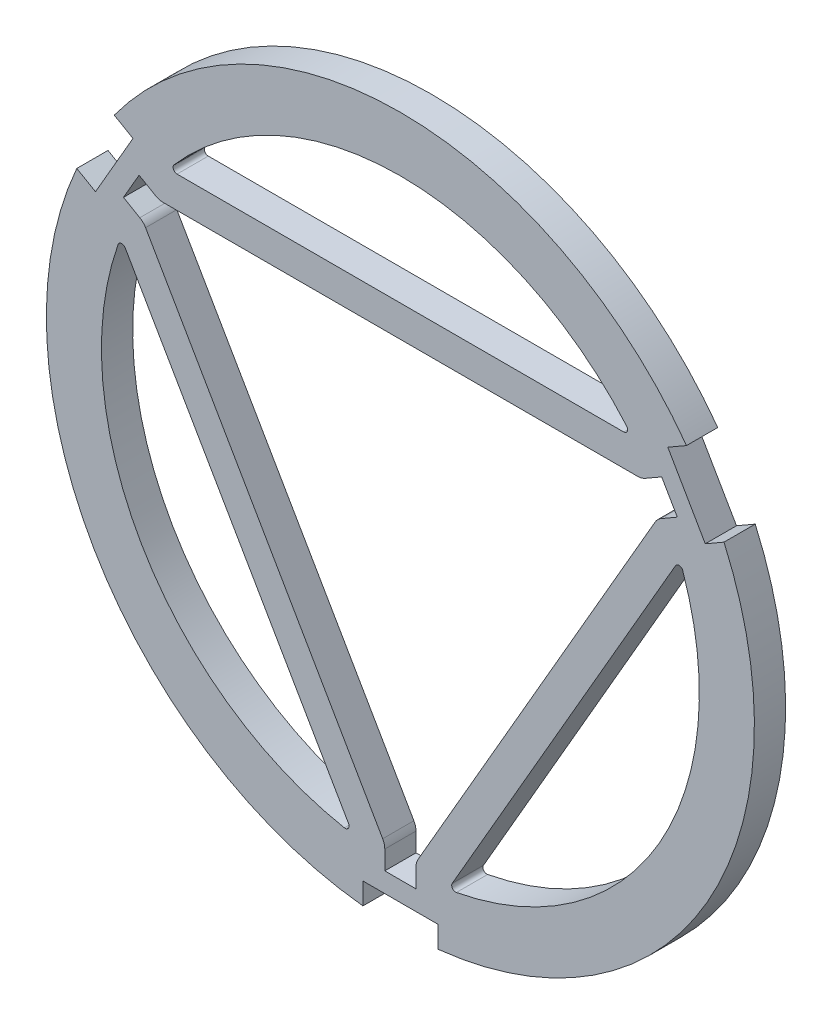
SolidWorks part; units mm, degrees
ref_plane "前基準面" through (0, 0, 0) normal (0, 0, 1) x (1, 0, 0)
ref_plane "上基準面" through (0, 0, 0) normal (0, 1, 0) x (1, 0, 0)
ref_plane "右基準面" through (0, 0, 0) normal (1, 0, 0) x (0, 0, -1)
sketch "Sketch1" plane through (0, 0, 0) normal (0, 0, 1) x (1, 0, 0)
  line L0 (0, 0) -> (0, 26.428) construction
  line L1 (0, 0) -> (-22.8874, 13.214) construction
  line L2 (0, 0) -> (-22.8874, -13.214) construction
  line L3 (-14.7309, 12) -> (14.7309, 12)
  line L4 (-15.3361, 10) -> (15.3361, 10)
  line L5 (-3.0268, -18.7574) -> (-17.7578, 6.7574)
  line L6 (-0.9922, -18.2815) -> (-16.3283, 8.2815)
  line L7 (0, 0) -> (0, -26.428) construction
  line L8 (0, 0) -> (22.8874, -13.214) construction
  line L9 (-22.2843, 12) -> (29.5995, 12) construction
  line L10 (-22.2843, 10) -> (29.5995, 10) construction
  line L11 (16.3283, 8.2815) -> (0.9922, -18.2815)
  line L12 (0, 0) -> (22.8874, 13.214) construction
  line L13 (16.4545, 9.5) -> (25.2108, 14.5555) construction
  line L14 (19.3772, 8.4378) -> (20.5668, 9.1246)
  line L15 (17.7578, 6.7574) -> (3.0268, -18.7574)
  line L16 (16.9959, 12.5622) -> (18.1855, 13.249)
  line L17 (15.2639, 11.5622) -> (15.9584, 10.3593) construction
  line L18 (16.9959, 12.5622) -> (19.3772, 8.4378)
  line L19 (15.2639, 11.5622) -> (24.0202, 16.6177) construction
  line L20 (17.6451, 7.4378) -> (26.4014, 12.4932) construction
  line L21 (2.3813, -21) -> (2.3813, -22.3736)
  line L22 (2.3813, -21) -> (-2.3812, -21)
  line L23 (-2.3812, -21) -> (-2.3812, -22.3736)
  line L24 (-19.3772, 8.4378) -> (-20.5668, 9.1246)
  line L25 (-19.3772, 8.4378) -> (-16.9959, 12.5622)
  line L26 (-16.9959, 12.5622) -> (-18.1855, 13.249)
  line L27 (16.9506, 8.6407) -> (17.6451, 7.4378) construction
  line L28 (15.2639, 11.5622) -> (17.6451, 7.4378) construction
  line L29 (16.6079, 10.7343) -> (17.6001, 9.0157)
  line L30 (15.3361, 10) -> (16.6079, 10.7343)
  line L31 (15.9134, 11.9372) -> (18.2946, 7.8128) construction
  line L32 (16.3283, 8.2815) -> (17.6001, 9.0157)
  line L33 (0.9922, -18.2815) -> (0.9922, -19.75)
  line L34 (0.9922, -19.75) -> (-0.9922, -19.75)
  line L35 (-0.9922, -18.2815) -> (-0.9922, -19.75)
  line L36 (-16.3283, 8.2815) -> (-17.6001, 9.0157)
  line L37 (-17.6001, 9.0157) -> (-16.6079, 10.7343)
  line L38 (-15.3361, 10) -> (-16.6079, 10.7343)
  arc A0 (18.1855, 13.249) -> (-18.1855, 13.249) centre (0, 0) ccw
  arc A3 (-17.7578, 6.7574) -> (-3.0268, -18.7574) centre (0, 0) ccw
  arc A4 (14.7309, 12) -> (-14.7309, 12) centre (0, 0) ccw
  arc A7 (3.0268, -18.7574) -> (17.7578, 6.7574) centre (0, 0) ccw
  arc A9 (-20.5668, 9.1246) -> (-2.3812, -22.3736) centre (0, 0) ccw
  arc A10 (2.3813, -22.3736) -> (20.5668, 9.1246) centre (0, 0) ccw
  point P12 (0, 19)
  dimension "D1" = 3.5
  dimension "D3" = 7
  dimension "D8" = 3
  dimension "D4" = 2
  dimension "D5" = 2.3813
  dimension "D6" = 2.3813
  dimension "D7" = 2
  dimension "D10" = 0.75
  dimension "D2" = 6
extrude "Boss-Extrude1" add sketch "Sketch1" along normal blind 1.9844
fillet "Fillet1" radius 0.25 6 edges at (-17.7578, 6.7574, 0.9922) (-3.0268, -18.7574, 0.9922) (17.7578, 6.7574, 0.9922) (3.0268, -18.7574, 0.9922) (-14.7309, 12, 0.9922) (14.7309, 12, 0.9922)
fillet "Fillet2" radius 1 6 edges at (-15.3361, 10, 0.9922) (-16.3283, 8.2815, 0.9922) (-0.9922, -18.2815, 0.9922) (0.9922, -18.2815, 0.9922) (16.3283, 8.2815, 0.9922) (15.3361, 10, 0.9922)
